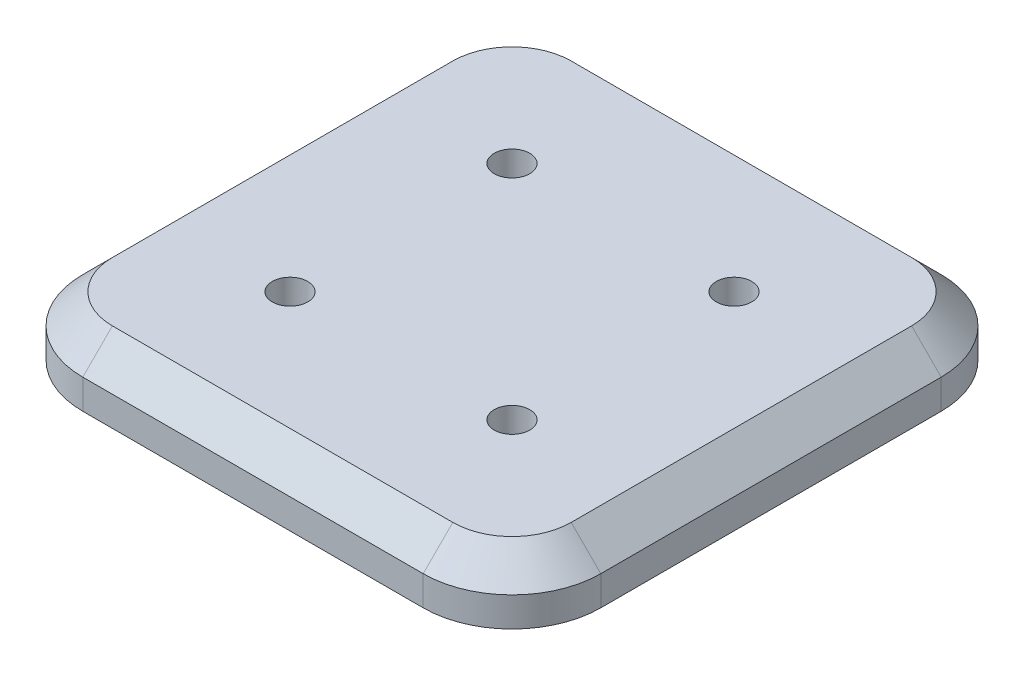
SolidWorks part; units mm, degrees
ref_plane "Front Plane" through (0, 0, 0) normal (0, 0, 1) x (1, 0, 0)
ref_plane "Top Plane" through (0, 0, 0) normal (0, 1, 0) x (1, 0, 0)
ref_plane "Right Plane" through (0, 0, 0) normal (1, 0, 0) x (0, 0, -1)
sketch "Sketch1" plane through (0, 0, 0) normal (0, 1, 0) x (1, 0, 0)
  line L0 (-57.5, 87.5) -> (57.5, 87.5)
  line L1 (87.5, 57.5) -> (87.5, -57.5)
  line L2 (57.5, -87.5) -> (-57.5, -87.5)
  line L3 (-87.5, -57.5) -> (-87.5, 57.5)
  arc A0 (-57.5, -87.5) -> (-87.5, -57.5) centre (-57.5, -57.5) cw
  arc A1 (87.5, -57.5) -> (57.5, -87.5) centre (57.5, -57.5) cw
  arc A2 (57.5, 87.5) -> (87.5, 57.5) centre (57.5, 57.5) cw
  arc A3 (-57.5, 87.5) -> (-87.5, 57.5) centre (-57.5, 57.5) ccw
  point P4 (0, 87.5)
  point P5 (-87.5, 0)
  point P13 (87.5, 87.5)
  point P16 (-87.5, 87.5)
  dimension "D2" = 30
  dimension "D1" = 175
extrude "Boss-Extrude1" add sketch "Sketch1" along normal mid plane 20
chamfer "Chamfer1" distance 10 angle 45 8 edges at (-87.5, 10, 0) (-78.7132, 10, -78.7132) (0, 10, -87.5) (78.7132, 10, -78.7132) (87.5, 10, 0) (78.7132, 10, 78.7132) (0, 10, 87.5) (-78.7132, 10, 78.7132)
sketch "Sketch2" plane through (0, 10, 0) normal (0, 1, 0) x (1, 0, 0)
  line L0 (37.5, 87.5) -> (37.5, -87.5) construction
  line L3 (-57.5, 87.5) -> (57.5, 87.5) construction
  line L4 (57.5, -87.5) -> (-57.5, -87.5) construction
  line L5 (-87.5, -57.5) -> (-87.5, 57.5) construction
  line L6 (-87.5, 37.5) -> (87.5, 37.5) construction
  line L7 (87.5, 57.5) -> (87.5, -57.5) construction
  line L8 (-148.0334, 0) -> (87.5, 0) construction
  line L9 (0, 87.5) -> (0, -87.5) construction
  circle A0 centre (37.5, 37.5) radius 6
  circle A1 centre (-37.5, 37.5) radius 6
  circle A2 centre (37.5, -37.5) radius 6
  circle A3 centre (-37.5, -37.5) radius 6
  dimension "D1" = 50
  dimension "D2" = 50
extrude "Cut-Extrude1" cut sketch "Sketch2" against normal offset from surface (10 mm away) 10 up to face at (0, 10, 0)
sketch "Sketch3" plane through (0, -10, 0) normal (0, -1, 0) x (1, 0, 0)
  line L0 (62.5, 87.5) -> (62.5, -87.5) construction
  line L1 (-57.5, 87.5) -> (57.5, 87.5) construction
  line L2 (57.5, -87.5) -> (-57.5, -87.5) construction
  line L3 (-87.5, 62.5) -> (87.5, 62.5) construction
  line L4 (-87.5, -57.5) -> (-87.5, 57.5) construction
  line L5 (87.5, 57.5) -> (87.5, -57.5) construction
  line L6 (0, 87.5) -> (0, -87.5) construction
  line L7 (-87.5, 0) -> (87.5, 0) construction
  circle A0 centre (62.5, 62.5) radius 6
  circle A1 centre (-62.5, 62.5) radius 6
  circle A2 centre (62.5, -62.5) radius 6
  circle A3 centre (-62.5, -62.5) radius 6
  dimension "D1" = 25
  dimension "D2" = 25
extrude "Cut-Extrude2" cut sketch "Sketch3" against normal offset from surface (10 mm away) 10 up to face at (0, -10, 0)
